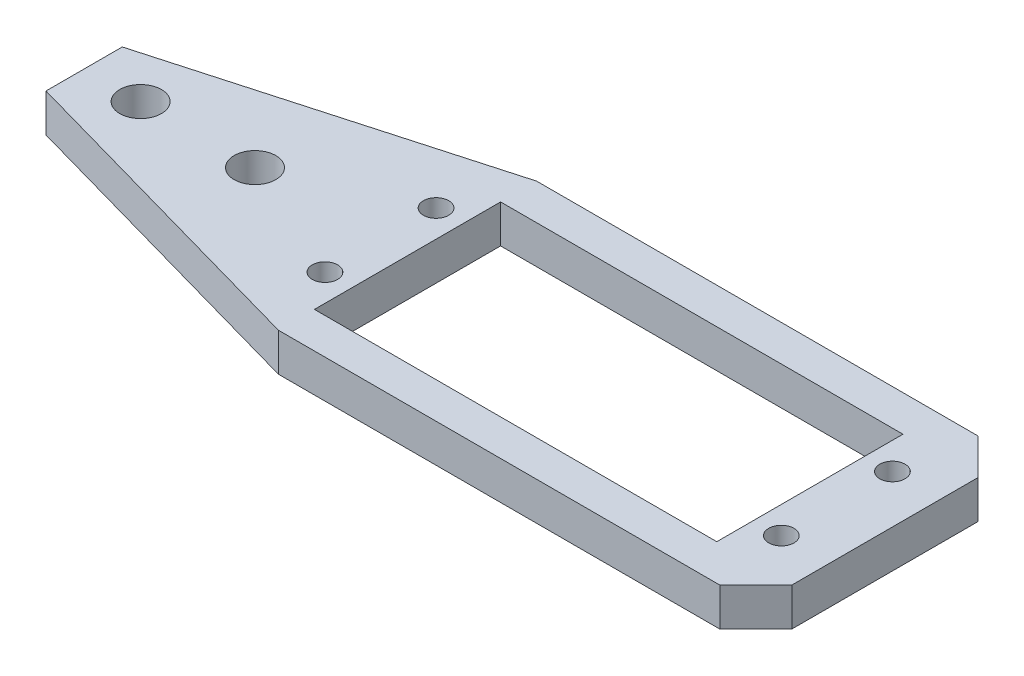
SolidWorks part; units mm, degrees
ref_plane "Front Plane" through (0, 0, 0) normal (0, 0, 1) x (1, 0, 0)
ref_plane "Top Plane" through (0, 0, 0) normal (0, 1, 0) x (1, 0, 0)
ref_plane "Right Plane" through (0, 0, 0) normal (1, 0, 0) x (0, 0, -1)
sketch "Sketch1" plane through (0, 0, 0) normal (0, 1, 0) x (1, 0, 0)
  line L0 (-12.825, 0) -> (54.175, 0) construction
  line L1 (60.675, -21.5) -> (-12.825, -21.5)
  line L2 (66.675, -15.5) -> (66.675, 15.5)
  line L3 (60.675, 21.5) -> (-12.825, 21.5)
  line L4 (-66.675, -6.35) -> (-66.675, 6.35)
  line L5 (66.675, -21.5) -> (-66.675, 21.5) construction
  line L6 (66.675, 21.5) -> (-66.675, -21.5) construction
  line L7 (54.175, -15.5) -> (-12.825, -15.5)
  line L8 (54.175, -15.5) -> (54.175, 15.5)
  line L9 (54.175, 15.5) -> (-12.825, 15.5)
  line L10 (-12.825, -15.5) -> (-12.825, 15.5)
  line L11 (54.175, -15.5) -> (-12.825, 15.5) construction
  line L12 (54.175, 15.5) -> (-12.825, -15.5) construction
  line L13 (20.675, 15.5) -> (20.675, -15.5) construction
  line L14 (-66.675, 0) -> (-12.825, 0) construction
  line L15 (-66.675, 6.35) -> (-12.825, 21.5)
  line L16 (-66.675, -6.35) -> (-12.825, -21.5)
  line L17 (66.675, -15.5) -> (60.675, -21.5)
  line L18 (60.675, 21.5) -> (66.675, 15.5)
  circle A0 centre (58.675, 9.25) radius 2.1082
  circle A1 centre (58.675, -9.25) radius 2.1082
  circle A2 centre (-17.325, -9.25) radius 2.1082
  circle A3 centre (-17.325, 9.25) radius 2.1082
  circle A4 centre (-57.275, 0) radius 3.475
  circle A5 centre (-38.225, 0) radius 3.475
  point P0 (0, 0)
  point P6 (20.675, 0)
  point P26 (-66.675, 6.35)
  point P29 (-66.675, -6.35)
  dimension "D5" = 4.2164
  dimension "D9" = 2
  dimension "D1" = 133.35
  dimension "D2" = 43
  dimension "D3" = 67
  dimension "D4" = 31
  dimension "D6" = 9.25
  dimension "D7" = 4.5
  dimension "D8" = 8
  dimension "D10" = 25.4
  dimension "D11" = 6.35
extrude "Boss-Extrude1" add sketch "Sketch1" along normal blind 6.35
